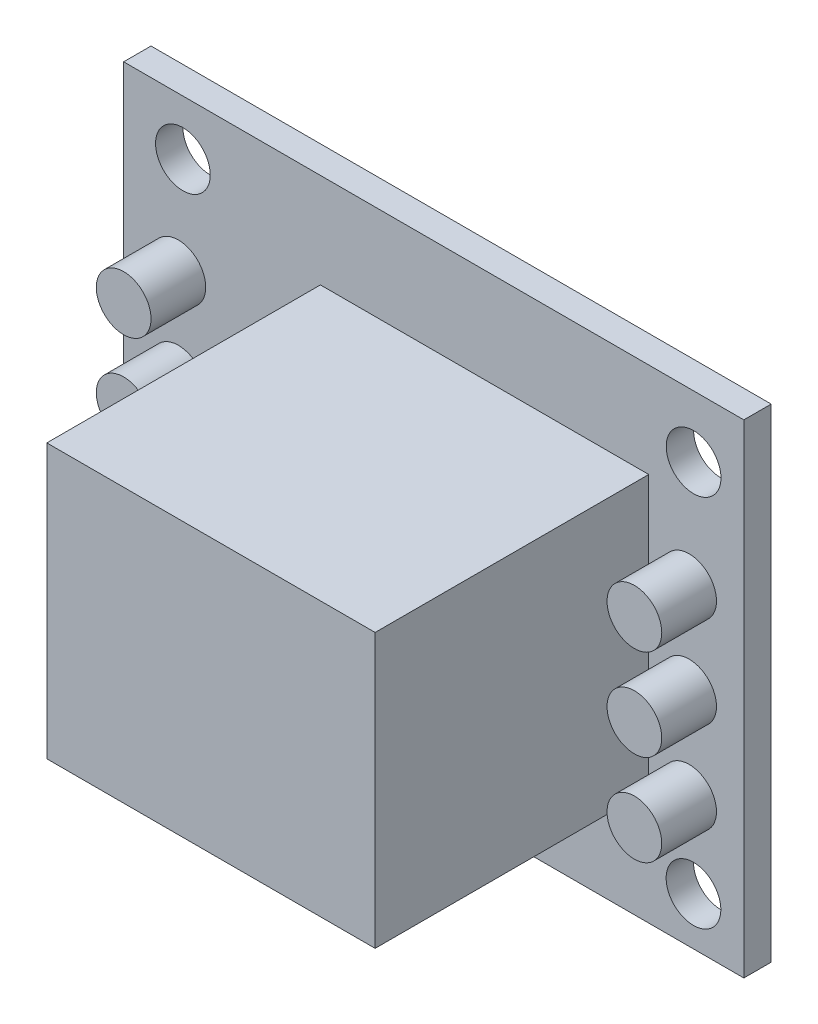
SolidWorks part; units mm, degrees
ref_plane "前基準面" through (0, 0, 0) normal (0, 0, 1) x (1, 0, 0)
ref_plane "上基準面" through (0, 0, 0) normal (0, 1, 0) x (1, 0, 0)
ref_plane "右基準面" through (0, 0, 0) normal (1, 0, 0) x (0, 0, -1)
sketch "草圖1" plane through (0, 0, 0) normal (0, 0, 1) x (1, 0, 0)
  line L1 (-14.7199, 13.4588) -> (19.2801, 13.4588)
  line L2 (-14.7199, 13.4588) -> (-14.7199, -13.0412)
  line L3 (-14.7199, -13.0412) -> (19.2801, -13.0412)
  line L4 (19.2801, 13.4588) -> (19.2801, -13.0412)
  circle A0 centre (-11.4722, 10.4588) radius 1.5
  circle A1 centre (-11.4772, -10.0412) radius 1.5
  circle A2 centre (16.5201, -10.4262) radius 1.5
  circle A3 centre (16.5251, 10.0738) radius 1.5
  dimension "D3" = 3
  dimension "D4" = 3
  dimension "D5" = 3
  dimension "D6" = 3
  dimension "D7" = 28
  dimension "D8" = 28
  dimension "D9" = 20.5
  dimension "D10" = 20.5
  dimension "D11" = 2.615
  dimension "D12" = 2.755
  dimension "D13" = 2.76
  dimension "D14" = 3
  dimension "D1" = 26.5
  dimension "D2" = 34
extrude "填料-伸長1" add sketch "草圖1" along normal blind 1.5
sketch "草圖2" plane through (0, 0, 1.5) normal (0, 0, 1) x (1, 0, 0)
  line L0 (19.2801, 13.4588) -> (-14.7199, 13.4588) construction
  line L1 (-3.9333, 8.2588) -> (14.0667, 8.2588)
  line L2 (-3.9333, 8.2588) -> (-3.9333, -6.7412)
  line L3 (-3.9333, -6.7412) -> (14.0667, -6.7412)
  line L4 (14.0667, 8.2588) -> (14.0667, -6.7412)
  dimension "D1" = 15
  dimension "D2" = 18
  dimension "D3" = 5.2
extrude "填料-伸長2" add sketch "草圖2" along normal blind 15
sketch "草圖3" plane through (0, 0, 1.5) normal (0, 0, 1) x (1, 0, 0)
  line L0 (-14.7199, 13.4588) -> (-14.7199, -13.0412) construction
  line L1 (19.2801, -13.0412) -> (19.2801, 13.4588) construction
  circle A0 centre (-11.7199, 5) radius 1.5
  circle A1 centre (-11.7199, 0) radius 1.5
  circle A2 centre (-11.7199, -5) radius 1.5
  circle A3 centre (16.2801, 4.1007) radius 1.5
  circle A4 centre (16.2801, -0.8993) radius 1.5
  circle A5 centre (16.2801, -5.8993) radius 1.5
  dimension "D1" = 3
  dimension "D5" = 3
  dimension "D6" = 3
  dimension "D7" = 3
  dimension "D8" = 5
  dimension "D9" = 5
  dimension "D10" = 5
  dimension "D11" = 5
  dimension "D2" = 3
  dimension "D3" = 3
  dimension "D4" = 3
extrude "填料-伸長3" add sketch "草圖3" along normal blind 3
